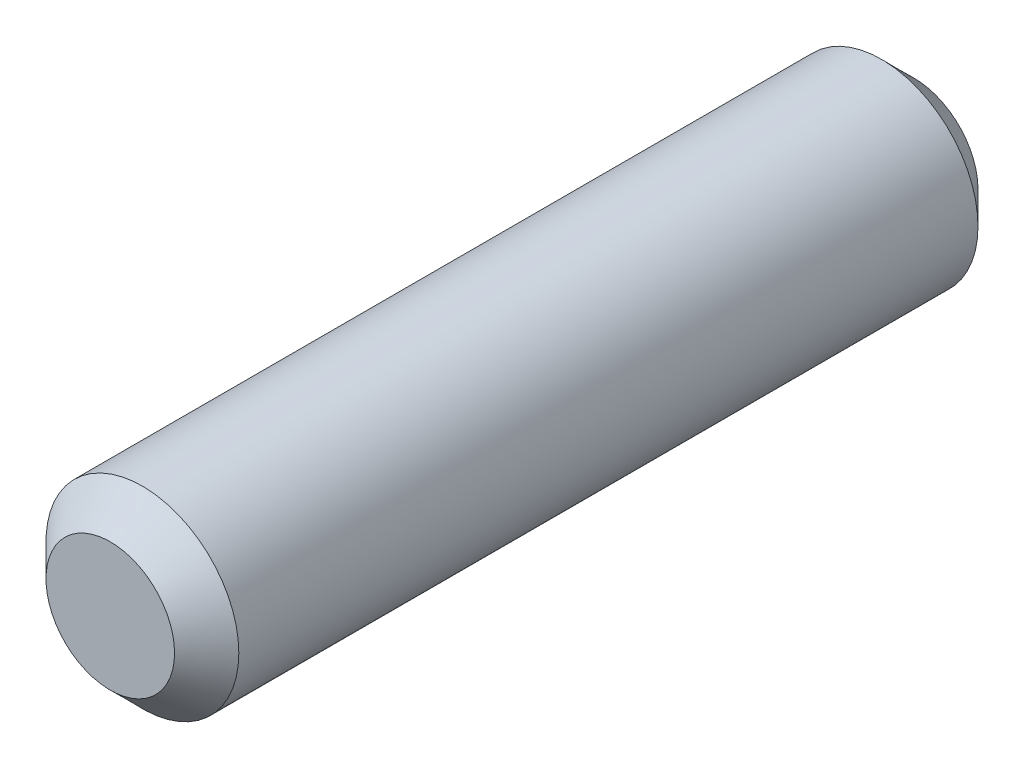
SolidWorks part; units mm, degrees
material "SUS304"
ref_plane "前视基准面" through (0, 0, 0) normal (0, 0, 1) x (1, 0, 0)
ref_plane "上视基准面" through (0, 0, 0) normal (0, 1, 0) x (1, 0, 0)
ref_plane "右视基准面" through (0, 0, 0) normal (1, 0, 0) x (0, 0, -1)
sketch "草图1" plane through (0, 0, 0) normal (0, 0, 1) x (1, 0, 0)
  circle A0 centre (0, 0) radius 3
  dimension "D1" = 6
extrude "拉伸1" add sketch "草图1" along normal blind 25
chamfer "倒角1" distance 1 angle 45 2 edges at (3, 0, 0) (3, 0, 25)
